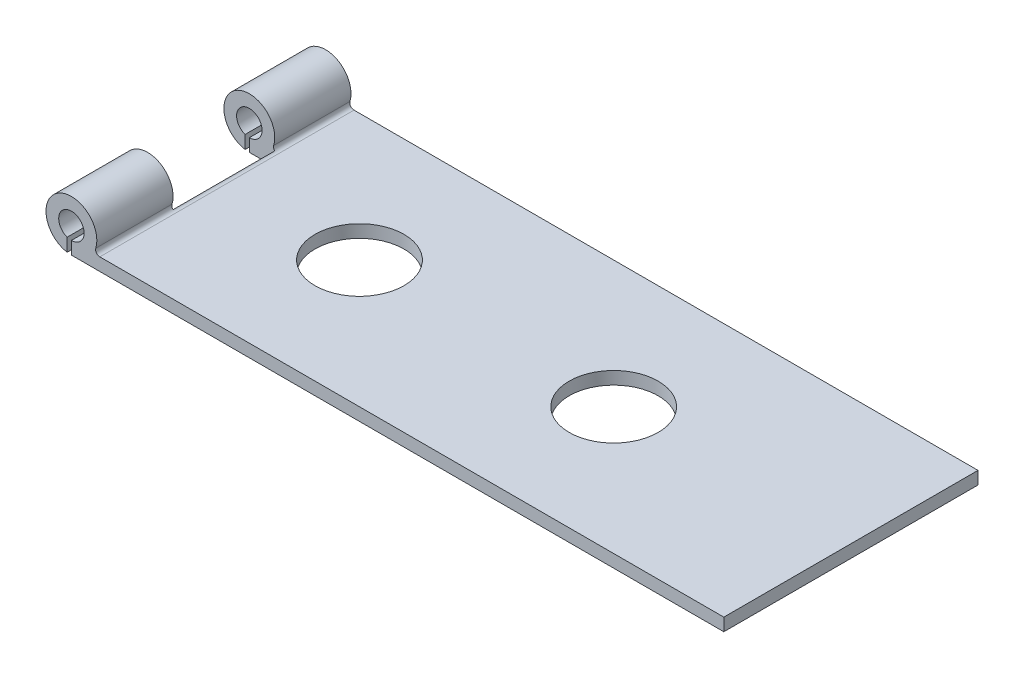
SolidWorks part; units mm, degrees
ref_plane "前视基准面" through (0, 0, 0) normal (0, 0, 1) x (1, 0, 0)
ref_plane "上视基准面" through (0, 0, 0) normal (0, 1, 0) x (1, 0, 0)
ref_plane "右视基准面" through (0, 0, 0) normal (1, 0, 0) x (0, 0, -1)
sketch "草图1" plane through (0, 0, 0) normal (0, 0, 1) x (1, 0, 0)
  line L0 (0, -55) -> (0, 55) construction
  line L1 (0, -3) -> (77, -3)
  line L2 (0, -3) -> (0, -1.5) construction
  line L3 (3.3541, -1.5) -> (77, -1.5)
  line L4 (77, -3) -> (77, -1.5)
  line L5 (0, -1.5) -> (2.5981, -1.5) construction
  arc A0 (2.8749, -0.8571) -> (0, -3) centre (0, 0) ccw
  circle A1 centre (0, 0) radius 1.5
  arc A2 (0, -3) -> (2.5981, -1.5) centre (0, 0) ccw construction
  arc A3 (2.8749, -0.8571) -> (3.3541, -1.5) centre (3.3541, -1) ccw
  point P8 (0, -3)
  dimension "D1" = 6
  dimension "D2" = 3
  dimension "D5" = 0.5
  dimension "D3" = 77
  dimension "D4" = 1.5
extrude "凸台-拉伸1" add sketch "草图1" along normal mid plane 30
sketch "草图2" plane through (0, -1.5, 0) normal (0, 1, 0) x (1, 0, 0)
  line L0 (0, -3.3) -> (0, 3.3) construction
  line L1 (-3, -6) -> (3, -6)
  line L2 (-3, -6) -> (-3, 6)
  line L3 (-3, 6) -> (3, 6)
  line L4 (3, -6) -> (3, 6)
  line L5 (-3, -6) -> (3, 6) construction
  line L6 (-3, 6) -> (3, -6) construction
  point P0 (0, 0)
  dimension "D1" = 12
  dimension "D2" = 3
extrude "切除-拉伸2" cut sketch "草图2" against normal through all both and the other way through all
sketch "草图3" plane through (0, 0, 15) normal (0, 0, 1) x (1, 0, 0)
  line L1 (0, 0) -> (-0.5, 0)
  line L2 (0, 0) -> (0, -10)
  line L3 (0, -10) -> (-0.5, -10)
  line L4 (-0.5, 0) -> (-0.5, -10)
  dimension "D1" = 10
  dimension "D2" = 0.5
extrude "切除-拉伸3" cut sketch "草图3" against normal through all both and the other way through all
sketch "草图4" plane through (0, -1.5, 0) normal (0, 1, 0) x (1, 0, 0)
  line L0 (-7.15, 0) -> (7.15, 0) construction
  circle A0 centre (19, 0) radius 5.25
  circle A1 centre (49, 0) radius 5.25
  point P8 (11.0683, 5.2845)
  dimension "D1" = 10.5
  dimension "D2" = 10.5
  dimension "D3" = 30
  dimension "D4" = 19
extrude "切除-拉伸4" cut sketch "草图4" against normal through all both and the other way through all
